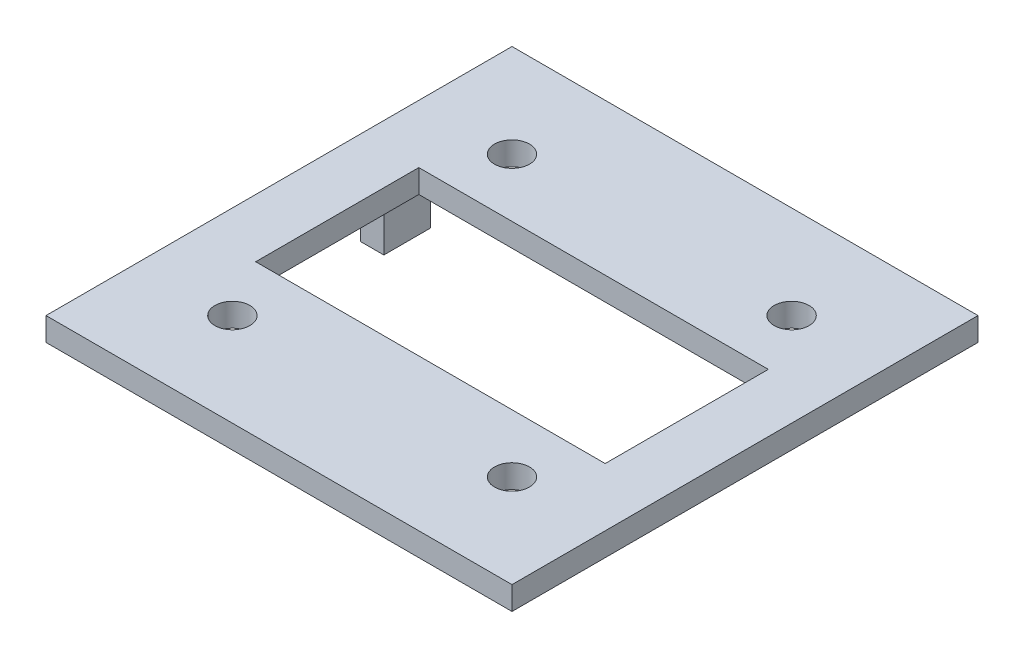
SolidWorks part; units mm, degrees
ref_plane "Front Plane" through (0, 0, 0) normal (0, 0, 1) x (1, 0, 0)
ref_plane "Top Plane" through (0, 0, 0) normal (0, 1, 0) x (1, 0, 0)
ref_plane "Right Plane" through (0, 0, 0) normal (1, 0, 0) x (0, 0, -1)
sketch "Sketch2" plane through (0, 0, 0) normal (0, 1, 0) x (1, 0, 0)
  line L1 (-20, -20) -> (20, -20)
  line L2 (-20, -20) -> (-20, 20)
  line L3 (-20, 20) -> (20, 20)
  line L4 (20, -20) -> (20, 20)
  line L5 (-20, -20) -> (20, 20) construction
  line L6 (-20, 20) -> (20, -20) construction
  line L7 (-15, -7.0006) -> (15, -7.0006)
  line L8 (-15, -7.0006) -> (-15, 7.0006)
  line L9 (-15, 7.0006) -> (15, 7.0006)
  line L10 (15, -7.0006) -> (15, 7.0006)
  line L11 (-15, -7.0006) -> (15, 7.0006) construction
  line L12 (-15, 7.0006) -> (15, -7.0006) construction
  line L17 (-12, -12) -> (12, 12) construction
  line L18 (-12, 12) -> (12, -12) construction
  circle A0 centre (-12, 12) radius 1.5
  circle A1 centre (12, 12) radius 1.5
  circle A2 centre (-12, -12) radius 1.5
  circle A3 centre (12, -12) radius 1.5
  point P0 (0, 0)
  point P6 (0, 0)
  point P11 (0, 0)
  dimension "D1" = 40
  dimension "D2" = 40
  dimension "D3" = 14.0012
  dimension "D4" = 30
  dimension "D5" = 24
  dimension "D6" = 24
extrude "Boss-Extrude1" add sketch "Sketch2" along normal blind 2
sketch "Sketch3" plane through (0, 0, 0) normal (0, -1, 0) x (1, 0, 0)
  line L0 (-20, -20) -> (-20, 20) construction
  line L1 (-18, -11) -> (18, -11)
  line L2 (-18, -11) -> (-18, 11)
  line L3 (-18, 11) -> (18, 11)
  line L4 (18, -11) -> (18, 11)
  line L5 (-18, -11) -> (18, 11) construction
  line L6 (-18, 11) -> (18, -11) construction
  line L7 (-18, 11) -> (-20, 11)
  line L8 (-18, 11) -> (-18, 7)
  line L9 (-18, 7) -> (-20, 7)
  line L10 (-20, 11) -> (-20, 7)
  line L12 (-18, -11) -> (-20, -11)
  line L13 (-18, -11) -> (-18, -7)
  line L14 (-18, -7) -> (-20, -7)
  line L15 (-20, -11) -> (-20, -7)
  point P0 (0, 0)
  line M9 (-20, 20) -> (-20, -20)
  dimension "D1" = 36
  dimension "D2" = 22
  dimension "D3" = 4
  dimension "D4" = 4
extrude "Boss-Extrude2" add sketch "Sketch3" along normal blind 6 contours L9 L2 L7 M9 | L2 L14 L12 M9
